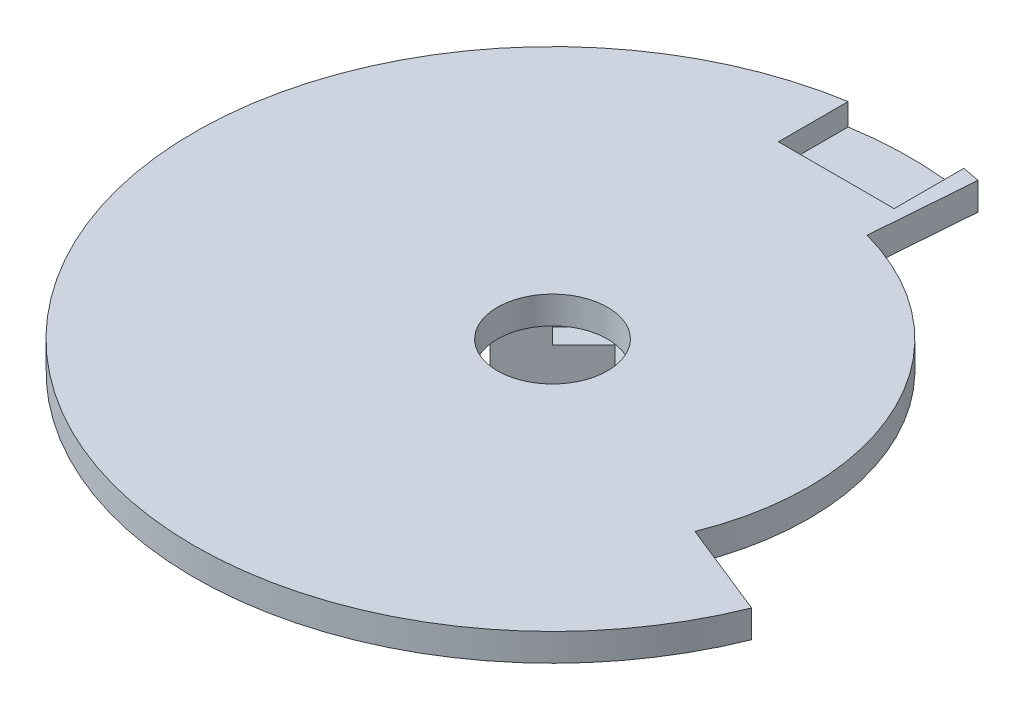
SolidWorks part; units mm, degrees
ref_plane "Front Plane" through (0, 0, 0) normal (0, 0, 1) x (1, 0, 0)
ref_plane "Top Plane" through (0, 0, 0) normal (0, 1, 0) x (1, 0, 0)
ref_plane "Right Plane" through (0, 0, 0) normal (1, 0, 0) x (0, 0, -1)
sketch "Sketch1" plane through (0, 0, 0) normal (0, 1, 0) x (1, 0, 0)
  circle A0 centre (0, 0) radius 65
extrude "Boss-Extrude1" add sketch "Sketch1" along normal blind 5
sketch "Sketch2" plane through (0, 5, 0) normal (0, 1, 0) x (1, 0, 0)
  circle A0 centre (0, 0) radius 10
extrude "Cut-Extrude1" cut sketch "Sketch2" against normal blind 5
sketch "Sketch5" plane through (0, 5, 0) normal (0, 1, 0) x (1, 0, 0)
  line L0 (0, 65) -> (0, 47.5) construction
  line L1 (0, 47.5) -> (10.5, 47.5)
  line L2 (10.5, 47.5) -> (10.5, 65)
  line L3 (10.5, 65) -> (-10.5, 65)
  line L4 (-10.5, 65) -> (-10.5, 47.5)
  line L5 (-10.5, 47.5) -> (0, 47.5)
  circle A0 centre (0, 0) radius 65 construction
  dimension "D1" = 17.5
  dimension "D2" = 10.5
  dimension "D3" = 10.5
extrude "Cut-Extrude3" cut sketch "Sketch5" against normal blind 4
sketch "Sketch3" plane through (0, 5, 0) normal (0, 1, 0) x (1, 0, 0)
  line L5 (0, 0) -> (69.5373, -27.8895) construction
  line L6 (43.1582, -17.3096) -> (60.3287, -24.1961)
  line L7 (12.2285, 44.8633) -> (13.6712, 63.546)
  circle A0 centre (0, 0) radius 65 construction
  arc A1 (46.5, 0) -> (43.1582, -17.3096) centre (0, 0) cw
  arc A2 (65, 0) -> (60.3287, -24.1961) centre (0, 0) cw
  arc A5 (46.5, 0) -> (19.3772, 42.2703) centre (0, 0) ccw
  arc A6 (65, 0) -> (27.0864, 59.0875) centre (0, 0) ccw
  arc A7 (19.3772, 42.2703) -> (15.9024, 43.6963) centre (0, 0) ccw
  arc A8 (27.0864, 59.0875) -> (22.2291, 61.0808) centre (0, 0) ccw
  arc A9 (15.9024, 43.6963) -> (12.2285, 44.8633) centre (0, 0) ccw
  arc A10 (22.2291, 61.0808) -> (13.6712, 63.546) centre (0, 0) ccw
extrude "Cut-Extrude2" cut sketch "Sketch3" against normal through all
sketch "Sketch9" plane through (0, 0, 0) normal (0, -1, 0) x (1, 0, 0)
  line L0 (-13.7532, -2.4395) -> (-16.5817, -5.2679)
  line L1 (-13.7532, -2.4395) -> (-2.4395, -13.7532)
  line L6 (-10.9248, -10.9248) -> (15.5563, 15.5563) construction
  line L15 (-2.4395, -13.7532) -> (-5.2679, -16.5817)
  line L20 (-16.5817, -5.2679) -> (-5.2679, -16.5817)
  line L23 (9.8995, 21.2132) -> (7.0711, 18.3848)
  line L24 (9.8995, 21.2132) -> (21.2132, 9.8995)
  line L25 (21.2132, 9.8995) -> (18.3848, 7.0711)
  line L26 (7.0711, 18.3848) -> (18.3848, 7.0711)
  point P5 (0, 0)
  point P6 (0, 0)
  point P9 (0, 0)
  point P12 (0, 0)
  point P20 (-1.545, 1.545)
  point P25 (2.3158, 2.3158)
extrude "Boss-Extrude2" add sketch "Sketch9" along normal blind 11
sketch "Sketch10" plane through (0, -11, 0) normal (0, -1, 0) x (1, 0, 0)
  line L9 (-5.2679, -16.5817) -> (-16.5817, -5.2679)
  line L10 (-16.5817, -5.2679) -> (9.8995, 21.2132)
  line L11 (9.8995, 21.2132) -> (21.2132, 9.8995)
  line L12 (21.2132, 9.8995) -> (9.8995, 21.2132) construction
  line L13 (21.2132, 9.8995) -> (-5.2679, -16.5817)
  point P0 (0, 0)
extrude "Boss-Extrude3" add sketch "Sketch10" along normal blind 5
sketch "Sketch11" plane through (0, -16, 0) normal (0, -1, 0) x (1, 0, 0)
  line L0 (9.8995, 21.2132) -> (16.5817, -5.2679) construction
  line L1 (6.8059, 15.468) -> (15.468, 6.8059)
  line L2 (6.8059, 15.468) -> (-9.2808, -0.6187)
  line L3 (-9.2808, -0.6187) -> (-0.6187, -9.2808)
  line L4 (15.468, 6.8059) -> (-0.6187, -9.2808)
  line L5 (-7, 0) -> (7, 0) construction
  line L6 (0, -7) -> (0, 7) construction
  circle A0 centre (0, 0) radius 10 construction
  point P0 (0, 0)
  point P14 (0, 0)
  point P15 (0, 0)
  point P18 (0, 0)
extrude "Cut-Extrude4" cut sketch "Sketch11" against normal blind 5
sketch "Sketch12" plane through (0, -16, 0) normal (0, -1, 0) x (1, 0, 0)
  line L0 (-0.6187, -9.2808) -> (9.2808, -9.2808) construction
  line L9 (-4.1543, -12.8163) -> (-0.6187, -9.2808)
  line L12 (-12.8163, -4.1543) -> (-4.1543, -12.8163)
  line L14 (-0.6187, -9.2808) -> (-9.2808, -0.6187)
  line L16 (6.8059, 15.468) -> (-9.2808, -0.6187) construction
  line L17 (-9.2808, -0.6187) -> (-0.6187, -9.2808) construction
  line L18 (-9.2808, -0.6187) -> (-12.8163, -4.1543)
  line L19 (7.4246, -1.2374) -> (-1.2374, 7.4246) construction
  line L20 (-0.6187, -9.2808) -> (15.468, 6.8059) construction
  line L21 (6.8059, 15.468) -> (10.3414, 19.0035)
  line L22 (15.468, 6.8059) -> (6.8059, 15.468)
  line L23 (19.0035, 10.3414) -> (15.468, 6.8059)
  line L24 (10.3414, 19.0035) -> (19.0035, 10.3414)
  point P0 (0, 0)
extrude "Cut-Extrude5" cut sketch "Sketch12" against normal blind 2.5
sketch "Sketch16" plane through (0, 0, -47.5) normal (0, 0, -1) x (-1, 0, 0)
  line L0 (-10.5, 5) -> (-10.5, 3)
  line L1 (-10.5, 1) -> (-10.5, 5) construction
  line L2 (-10.5, 3) -> (10.5, 3)
  line L3 (10.5, 1) -> (10.5, 5) construction
  line L4 (10.5, 3) -> (10.5, 5)
  line L5 (10.5, 5) -> (-10.5, 5) construction
  line L6 (10.5, 5) -> (-10.5, 5)
sketch "Sketch17" plane through (5.6569, 0, -5.6569) normal (0.7071, 0, -0.7071) x (-0.7071, 0, -0.7071)
  line L0 (15.45, 0) -> (11.45, 0)
  line L1 (15.45, 0) -> (11.45, 0) construction
  line L2 (11.45, 0) -> (11.45, -4)
  line L3 (11.45, -11) -> (11.45, 0) construction
  line L4 (11.45, -4) -> (15.45, -4)
  line L5 (15.45, -16) -> (15.45, 0) construction
  line L6 (15.45, -4) -> (15.45, 0)
extrude "Boss-Extrude5" add sketch "Sketch16" along normal blind 4
extrude "Cut-Extrude8" cut sketch "Sketch17" against normal blind 8
sketch "Sketch20" plane through (0, 0, 0) normal (0, -1, 0) x (1, 0, 0)
  line L0 (0, -46.5) -> (0, -65)
  line L1 (-2.3305, -46.4416) -> (-3.2576, -64.9183)
  line L2 (-3.2576, -64.9183) -> (0, -65)
  arc A0 (0, -46.5) -> (-2.3305, -46.4416) centre (0, 0) cw
  arc A1 (0, -65) -> (-3.2576, -64.9183) centre (0, 0) cw
sketch "Sketch21" plane through (0, 0, 0) normal (0, -1, 0) x (1, 0, 0)
  line L1 (30.2618, 0) -> (40.1534, 0)
  line L2 (2.6205, -30.1482) -> (3.477, -40.0025)
  arc A0 (3.477, -40.0025) -> (40.1534, 0) centre (0, 0) ccw
  arc A2 (30.2618, 0) -> (2.6205, -30.1482) centre (0, 0) cw
sketch "Sketch22" plane through (0, 0, 0) normal (0, -1, 0) x (1, 0, 0)
  line L0 (21.2132, 9.8995) -> (35.3553, 24.0416)
  line L1 (35.3553, 24.0416) -> (42.4264, 16.9706)
  line L2 (42.4264, 16.9706) -> (-7.0711, -32.5269)
  line L3 (-7.0711, -32.5269) -> (-14.1421, -25.4558)
  line L4 (-14.1421, -25.4558) -> (21.2132, 9.8995)
extrude "Boss-Extrude6" add sketch "Sketch22" along normal blind 6.5
sketch "Sketch23" plane through (12.7279, 0, -12.7279) normal (0.7071, 0, -0.7071) x (-0.7071, 0, -0.7071)
  line L0 (25, 0) -> (-39, 0)
  line L1 (28, 0) -> (-42, 0) construction
  line L4 (25, 0) -> (25, -3.5)
  line L5 (25, -3.5) -> (-39, -3.5)
  line L6 (-39, -3.5) -> (-39, 0)
extrude "Cut-Extrude9" cut sketch "Sketch23" against normal blind 10
